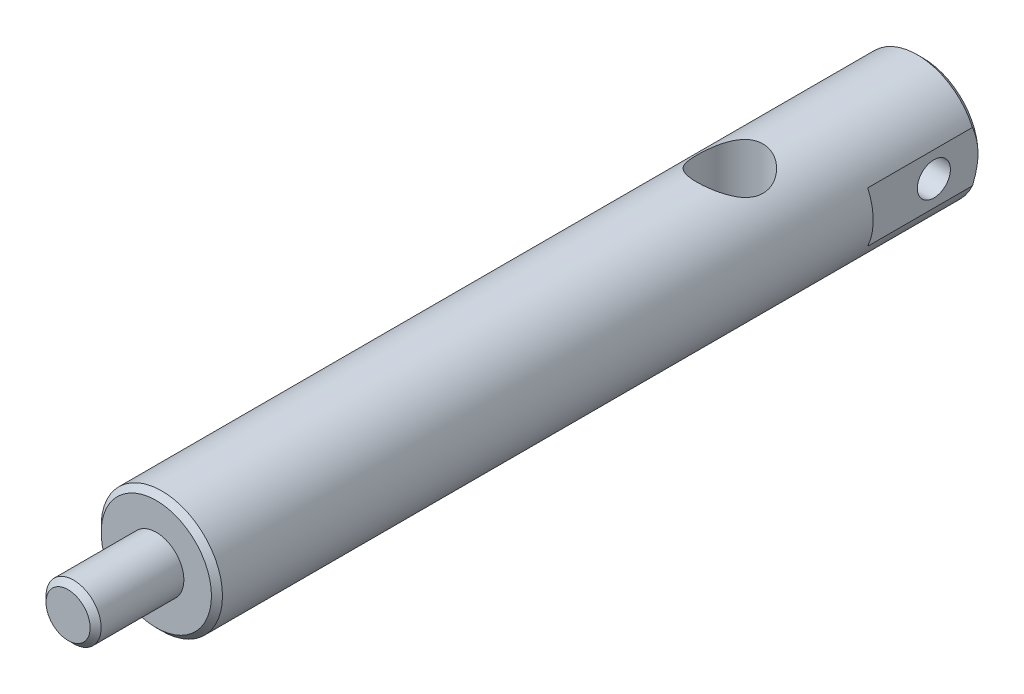
SolidWorks part; units mm, degrees
material "Q235A"
ref_plane "前视基准面" through (0, 0, 0) normal (0, 0, 1) x (1, 0, 0)
ref_plane "上视基准面" through (0, 0, 0) normal (0, 1, 0) x (1, 0, 0)
ref_plane "右视基准面" through (0, 0, 0) normal (1, 0, 0) x (0, 0, -1)
sketch "草图1" plane through (0, 0, 0) normal (0, 0, 1) x (1, 0, 0)
  circle A0 centre (0, 0) radius 5.5
  dimension "D1" = 11
extrude "拉伸1" add sketch "草图1" along normal blind 69.5
chamfer "倒角1" distance 0.5 angle 45 2 edges at (5.5, 0, 0) (5.5, 0, 69.5)
sketch "草图2" plane through (0, 0, 69.5) normal (0, 0, 1) x (1, 0, 0)
  circle A0 centre (0, 0) radius 2.5
  dimension "D1" = 5
extrude "拉伸2" add sketch "草图2" along normal blind 8
cosmetic thread "装饰螺纹线1" parameters "D2"=4
chamfer "倒角2" distance 0.5 angle 45 1 edges at (2.5, 0, 77.5)
hole_wizard "M4 螺纹孔1" [suppressed] positions "草图4" profile "草图3" tap size "M4" standard "GB"
sketch "草图4" plane through (0, 0, 0) normal (0, 0, -1) x (-1, 0, 0)
  point P1 (0, 0)
sketch "草图3" plane through (0, 0, 0) normal (1, 0, 0) x (0, 1, 0)
  line L0 (0, 0) -> (0, 11.0914)
  line L1 (0, 11.0914) -> (1.65, 10.1)
  line L2 (1.65, 10.1) -> (1.65, 0)
  line L5 (1.65, 0) -> (0, 0)
  line L10 (0, 11.0914) -> (-1.65, 10.1) construction
  line L11 (0, -6.35) -> (0, 107.95) construction
  dimension "螺纹孔钻头直径" = 3.3
  dimension "螺纹孔钻头深度" = 10.1
  dimension "导头角度" = 118
cosmetic thread "孔螺蚊线1" [suppressed] parameters "D1"=8, "D2"=4
chamfer "倒角3" [suppressed] distance 0.5 angle 45
sketch "草图5" plane through (0, 0, 0) normal (1, 0, 0) x (0, 0, -1)
  line L0 (0, 0) -> (-4, 0) construction
  circle A0 centre (-4, 0) radius 1.5
  dimension "D2" = 3
  dimension "D1" = 4
extrude "拉伸3" cut sketch "草图5" against normal mid plane 15
sketch "草图6" plane through (0, 0, 0) normal (0, 1, 0) x (1, 0, 0)
  line L0 (0, 0) -> (0, -17.5) construction
  circle A0 centre (0, -17.5) radius 3
  dimension "D1" = 6
  dimension "D2" = 17.5
extrude "拉伸4" cut sketch "草图6" against normal mid plane 15
chamfer "倒角4" [suppressed] distance 1 angle 45
sketch "草图7" plane through (0, 0, 0) normal (0, 0, 1) x (1, 0, 0)
  line L0 (0, 0) -> (5, 0) construction
  line L1 (5, 5) -> (7, 5)
  line L2 (5, 5) -> (5, -5)
  line L3 (5, -5) -> (7, -5)
  line L4 (7, 5) -> (7, -5)
  dimension "D1" = 5
  dimension "D2" = 10
  dimension "D3" = 2
extrude "拉伸5" cut sketch "草图7" along normal blind 10
mirror "镜向1" about plane through (0, 0, 0) normal (1, 0, 0) of "拉伸5"
